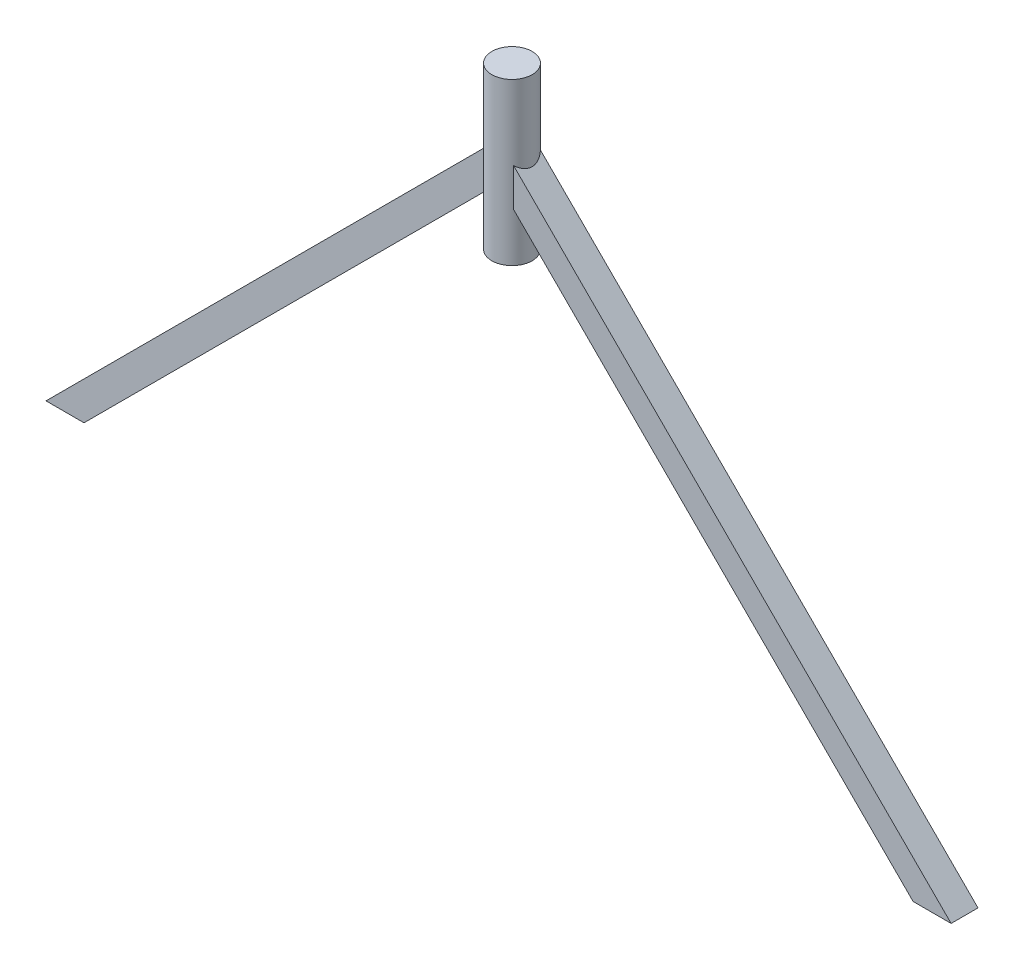
SolidWorks part; units mm, degrees
ref_plane "Front Plane" through (0, 0, 0) normal (0, 0, 1) x (1, 0, 0)
ref_plane "Top Plane" through (0, 0, 0) normal (0, 1, 0) x (1, 0, 0)
ref_plane "Right Plane" through (0, 0, 0) normal (1, 0, 0) x (0, 0, -1)
sketch "Sketch2" plane through (0, 0, 0) normal (0, 1, 0) x (1, 0, 0)
  circle A0 centre (0, 0) radius 19.05
  dimension "D1" = 38.1
extrude "Boss-Extrude1" add sketch "Sketch2" along normal blind 152.4
sketch "Sketch3" plane through (0, 0, 0) normal (0, 0, 1) x (1, 0, 0)
  line L0 (-6.0287, 90.0484) -> (11.9318, 72.0879)
  line L1 (-6.0287, 90.0484) -> (-409.7898, -313.7127)
  line L2 (11.9318, 72.0879) -> (-391.8293, -331.6732)
  line L3 (-409.7898, -313.7127) -> (-391.8293, -331.6732)
  line L4 (-19.05, 152.4) -> (-19.05, 0) construction
  line L5 (-391.8293, -331.6732) -> (-427.7503, -331.6732)
  line L6 (-427.7503, -331.6732) -> (-409.7898, -313.7127)
  line L7 (19.05, 152.4) -> (-19.05, 152.4) construction
  point P6 (-340.3267, -147.3931)
  point P11 (0, 85.5308)
  point P12 (0, 0)
  dimension "D1" = 135
  dimension "D2" = 25.4
  dimension "D3" = 484.0732
  dimension "D4" = 391.8293
extrude "Boss-Extrude2" add sketch "Sketch3" along normal mid plane 25.4 contours L6 L5 L3 | L1 L3 L2 L0
mirror "Mirror1" about plane through (0, 0, 0) normal (1, 0, 0) of "Boss-Extrude2"
